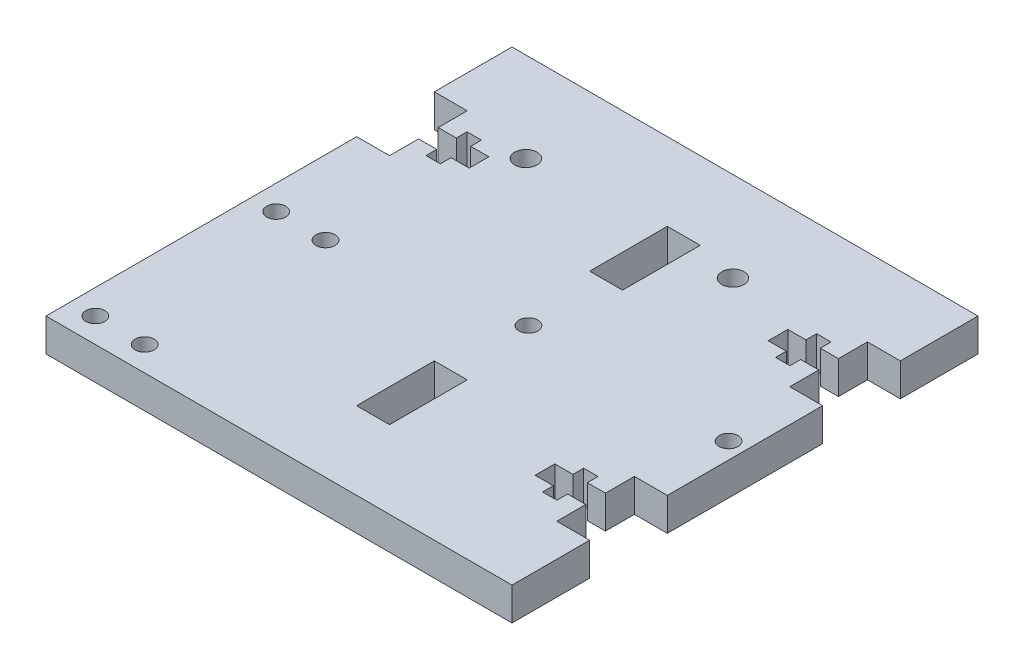
SolidWorks part; units mm, degrees
material "Beech"
ref_plane "Front Plane" through (0, 0, 0) normal (0, 0, 1) x (1, 0, 0)
ref_plane "Top Plane" through (0, 0, 0) normal (0, 1, 0) x (1, 0, 0)
ref_plane "Right Plane" through (0, 0, 0) normal (1, 0, 0) x (0, 0, -1)
sketch "Sketch1" plane through (0, 0, 0) normal (0, 1, 0) x (1, 0, 0)
  line L1 (-45, -45) -> (45, -45)
  line L2 (-45, -45) -> (-45, 45)
  line L3 (-45, 45) -> (45, 45)
  line L4 (45, -45) -> (45, 45)
  line L5 (-45, -45) -> (45, 45) construction
  line L6 (-45, 45) -> (45, -45) construction
  point P0 (0, 0)
  dimension "D1" = 90
  dimension "D2" = 90
extrude "Boss-Extrude1" add sketch "Sketch1" along normal blind 6.35
hole_wizard "#6 Clearance Hole1" positions "Sketch3" profile "Sketch4" hole size "#6" standard "ANSI Inch" end condition up to next
sketch "Sketch3" plane through (0, 6.35, 0) normal (0, 1, 0) x (1, 0, 0)
  line L0 (-45, 45) -> (-45, -45) construction
  line L1 (-45, -45) -> (45, -45) construction
  point P0 (-40.2375, -40.2375)
  dimension "D1" = 4.7625
  dimension "D2" = 4.7625
sketch "Sketch4" plane through (-40.2375, 6.35, 40.2375) normal (1, 0, 0) x (0, 0, 1)
  line L0 (0, 0) -> (0, 6.35)
  line L1 (0, 6.35) -> (1.8288, 6.35)
  line L2 (1.8288, 6.35) -> (1.8288, 0)
  line L5 (1.8288, 0) -> (0, 0)
  line L11 (0, -6.35) -> (0, 107.95) construction
  dimension "Thru Hole Dia." = 3.6576
  dimension "Thru Hole Depth" = 6.35
pattern_linear "LPattern1" count 2 spacing 34.925 along (0, 0, -1) count 2 spacing 9.525 along (1, 0, 0) of "#6 Clearance Hole1"
hole_wizard "#8 Clearance Hole1" positions "Sketch5" profile "Sketch6" hole size "#8" standard "ANSI Inch" end condition up to next
sketch "Sketch5" plane through (0, 6.35, 0) normal (0, 1, 0) x (1, 0, 0)
  line L0 (-25, 27.675) -> (15, 27.675) construction
  line L2 (-45, 45) -> (-45, -45) construction
  line L3 (-30.7125, -5.3125) -> (-30.7125, -40.2375) construction
  point P0 (-25, 27.675)
  point P2 (15, 27.675)
  point P22 (-30.7125, -22.775)
  dimension "D1" = 40
  dimension "D2" = 20
  dimension "D3" = 50.45
sketch "Sketch6" plane through (-25, 6.35, -27.675) normal (1, 0, 0) x (0, 0, 1)
  line L0 (0, 0) -> (0, 6.35)
  line L1 (0, 6.35) -> (2.1526, 6.35)
  line L2 (2.1526, 6.35) -> (2.1526, 0)
  line L5 (2.1526, 0) -> (0, 0)
  line L11 (0, -6.35) -> (0, 107.95) construction
  dimension "Thru Hole Dia." = 4.3053
  dimension "Thru Hole Depth" = 6.35
sketch "Sketch7" plane through (0, 6.35, 0) normal (0, 1, 0) x (1, 0, 0)
  line L1 (0, -30) -> (6.35, -30)
  line L2 (0, -30) -> (0, -15)
  line L3 (0, -15) -> (6.35, -15)
  line L4 (6.35, -30) -> (6.35, -15)
  line L5 (45, -45) -> (45, 45) construction
  line L6 (0, 15) -> (6.35, 15)
  line L7 (0, 15) -> (0, 30)
  line L8 (0, 30) -> (6.35, 30)
  line L9 (6.35, 15) -> (6.35, 30)
  line L10 (45, -30) -> (38.65, -30)
  line L11 (45, -30) -> (45, -15)
  line L12 (45, -15) -> (38.65, -15)
  line L13 (38.65, -30) -> (38.65, -15)
  line L14 (45, 15) -> (38.65, 15)
  line L15 (45, 15) -> (45, 30)
  line L16 (45, 30) -> (38.65, 30)
  line L17 (38.65, 15) -> (38.65, 30)
  line L18 (-45, 45) -> (-45, -45) construction
  line L19 (-45, -45) -> (45, -45) construction
  dimension "D1" = 45
  dimension "D2" = 6.35
  dimension "D3" = 6.35
  dimension "D4" = 30
  dimension "D5" = 15
  dimension "D6" = 15
  dimension "D7" = 15
extrude "Cut-Extrude1" cut sketch "Sketch7" against normal through all
hole_wizard "#6 Clearance Hole2" positions "Sketch8" profile "Sketch9" hole size "#6" standard "ANSI Inch" end condition up to next
sketch "Sketch8" plane through (0, 6.35, 0) normal (0, 1, 0) x (1, 0, 0)
  line L0 (3.175, -15) -> (3.175, 15) construction
  line L1 (6.35, -15) -> (0, -15) construction
  line L2 (0, 15) -> (6.35, 15) construction
  line L4 (41.825, 15) -> (41.825, -15) construction
  line L5 (38.65, 15) -> (45, 15) construction
  line L6 (45, -15) -> (38.65, -15) construction
  point P17 (3.175, 0)
  point P19 (41.825, 0)
sketch "Sketch9" plane through (41.825, 6.35, 0) normal (1, 0, 0) x (0, 0, 1)
  line L0 (0, 0) -> (0, 6.35)
  line L1 (0, 6.35) -> (1.8288, 6.35)
  line L2 (1.8288, 6.35) -> (1.8288, 0)
  line L5 (1.8288, 0) -> (0, 0)
  line L11 (0, -6.35) -> (0, 107.95) construction
  dimension "Thru Hole Dia." = 3.6576
  dimension "Thru Hole Depth" = 6.35
sketch "Sketch10" plane through (0, 6.35, 0) normal (0, 1, 0) x (1, 0, 0)
  line L0 (6.35, -22.5) -> (38.65, -22.5) construction
  line L1 (6.35, -30) -> (6.35, -15) construction
  line L2 (38.65, -15) -> (38.65, -30) construction
  line L3 (45, 0) -> (-45, 0) construction
  line L4 (45, -15) -> (45, 15) construction
  line L5 (-45, 45) -> (-45, -45) construction
  line L6 (28.871, -20.6014) -> (28.871, -24.3986)
  line L7 (38.65, -24.3986) -> (35.1496, -24.3986)
  line L8 (35.1496, -24.3986) -> (35.1496, -26.4688)
  line L9 (35.1496, -26.4688) -> (32.3714, -26.4688)
  line L10 (32.3714, -26.4688) -> (32.3714, -24.3986)
  line L11 (32.3714, -24.3986) -> (28.871, -24.3986)
  line L12 (38.65, -24.3986) -> (38.65, -20.6014)
  line L13 (32.3714, -20.6014) -> (28.871, -20.6014)
  line L14 (32.3714, -18.5312) -> (32.3714, -20.6014)
  line L15 (35.1496, -18.5312) -> (32.3714, -18.5312)
  line L16 (35.1496, -20.6014) -> (35.1496, -18.5312)
  line L17 (38.65, -20.6014) -> (35.1496, -20.6014)
  line L18 (38.65, 24.3986) -> (38.65, 20.6014)
  line L19 (38.65, 20.6014) -> (35.1496, 20.6014)
  line L20 (35.1496, 20.6014) -> (35.1496, 18.5312)
  line L21 (32.3714, 18.5312) -> (32.3714, 20.6014)
  line L22 (35.1496, 18.5312) -> (32.3714, 18.5312)
  line L23 (32.3714, 20.6014) -> (28.871, 20.6014)
  line L24 (28.871, 20.6014) -> (28.871, 24.3986)
  line L25 (32.3714, 24.3986) -> (28.871, 24.3986)
  line L26 (32.3714, 26.4688) -> (32.3714, 24.3986)
  line L27 (35.1496, 26.4688) -> (32.3714, 26.4688)
  line L28 (35.1496, 24.3986) -> (35.1496, 26.4688)
  line L29 (38.65, 24.3986) -> (35.1496, 24.3986)
  point P14 (28.871, -22.5)
  dimension "D1" = 3.7973
  dimension "D2" = 9.779
  dimension "D3" = 3.9688
  dimension "D4" = 2.7781
extrude "Cut-Extrude2" cut sketch "Sketch10" against normal through all
sketch "Sketch11" plane through (0, 6.35, 0) normal (0, 1, 0) x (1, 0, 0)
  line L0 (-45, 45) -> (-45, -45) construction
  line L5 (-45, 15) -> (-38.65, 15)
  line L6 (-45, 15) -> (-45, 30)
  line L7 (-45, 30) -> (-38.65, 30)
  line L8 (-38.65, 15) -> (-38.65, 20.6014)
  line L9 (0, 15) -> (6.35, 15) construction
  line L10 (6.35, 30) -> (0, 30) construction
  line L11 (-38.65, 20.6014) -> (-35.1496, 20.6014)
  line L12 (-35.1496, 20.6014) -> (-35.1496, 18.5312)
  line L13 (-35.1496, 18.5312) -> (-32.3714, 18.5312)
  line L14 (-32.3714, 18.5312) -> (-32.3714, 20.6014)
  line L15 (-32.3714, 20.6014) -> (-28.871, 20.6014)
  line L16 (-28.871, 20.6014) -> (-28.871, 24.3986)
  line L17 (28.871, 20.6014) -> (32.3714, 20.6014) construction
  line L18 (32.3714, 18.5312) -> (35.1496, 18.5312) construction
  line L19 (-28.871, 22.5) -> (-45, 22.5) construction
  line L20 (-32.3714, 24.3986) -> (-28.871, 24.3986)
  line L21 (-32.3714, 26.4687) -> (-32.3714, 24.3986)
  line L22 (-35.1496, 26.4687) -> (-32.3714, 26.4687)
  line L23 (-35.1496, 24.3986) -> (-35.1496, 26.4687)
  line L24 (-38.65, 24.3986) -> (-35.1496, 24.3986)
  line L25 (-38.65, 24.3986) -> (-38.65, 30)
  dimension "D3" = 6.35
  dimension "D4" = 9.779
  dimension "D5" = 2.7781
extrude "Cut-Extrude3" cut sketch "Sketch11" against normal through all
sketch "Sketch12" [suppressed] plane through (0, 6.35, 0) normal (0, 1, 0) x (1, 0, 0)
  line L1 (-45, -45) -> (-25.95, -45)
  line L2 (-45, -45) -> (-45, -0.55)
  line L3 (-45, -0.55) -> (-25.95, -0.55)
  line L4 (-25.95, -45) -> (-25.95, -0.55)
  dimension "D1" = 19.05
  dimension "D2" = 44.45
extrude "Cut-Extrude4" [suppressed] cut sketch "Sketch12" against normal through all
sketch "Sketch13" [suppressed] plane through (0, 6.35, 0) normal (0, 1, 0) x (1, 0, 0)
  circle A0 centre (15, 27.675) radius 2.1526 construction
  circle A1 centre (-25, 27.675) radius 2.1526 construction
  circle A2 centre (15, 27.675) radius 2.1526
  circle A3 centre (-25, 27.675) radius 2.1526
extrude "Boss-Extrude2" [suppressed] add sketch "Sketch13" against normal up to surface (6.35 mm away)
sketch "Sketch14" [suppressed] plane through (0, 6.35, 0) normal (0, 1, 0) x (1, 0, 0)
  line L0 (10.5625, 37.55) -> (17.5625, 37.55) construction
  line L1 (-25.95, -0.55) -> (-45, -0.55) construction
  line L2 (-25.95, -45) -> (-25.95, -0.55) construction
  circle A0 centre (10.5625, 37.55) radius 1.4732
  circle A1 centre (17.5625, 37.55) radius 1.4732
  dimension "D2" = 2.9464
  dimension "D1" = 7
  dimension "D3" = 38.1
  dimension "D4" = 36.5125
extrude "Cut-Extrude5" [suppressed] cut sketch "Sketch14" against normal through all
